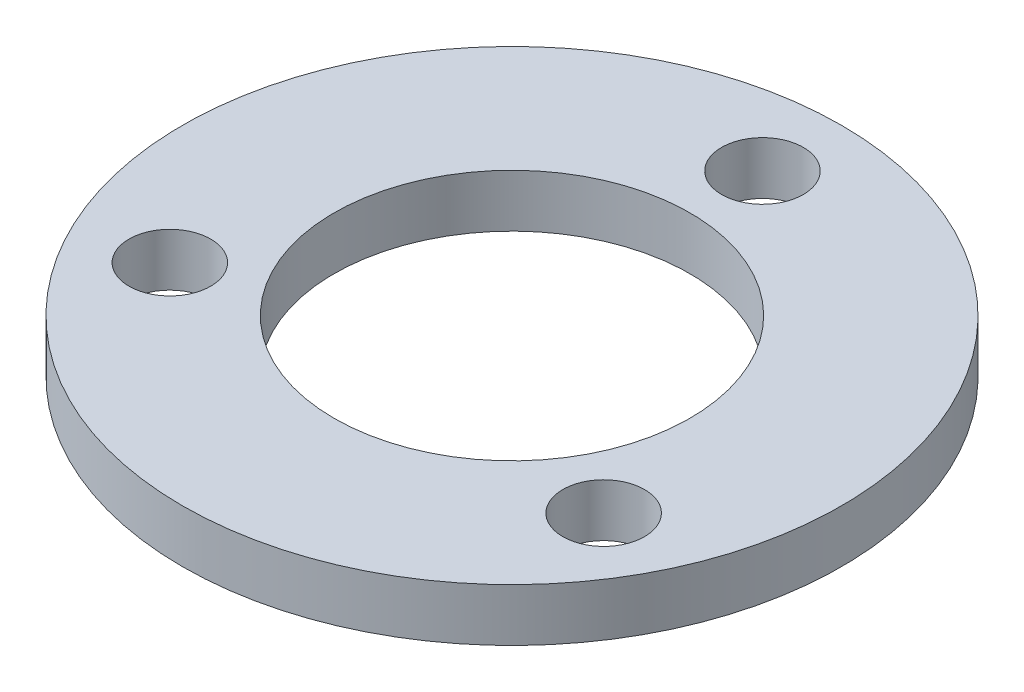
SolidWorks part; units mm, degrees
material "环氧树脂,未充填"
ref_plane "前视基准面" through (0, 0, 0) normal (0, 0, 1) x (1, 0, 0)
ref_plane "上视基准面" through (0, 0, 0) normal (0, 1, 0) x (1, 0, 0)
ref_plane "右视基准面" through (0, 0, 0) normal (1, 0, 0) x (0, 0, -1)
sketch "草图2" plane through (0, 0, 0) normal (0, 1, 0) x (1, 0, 0)
  circle A0 centre (0, 0) radius 6.75
  circle A1 centre (0, 0) radius 12.5
  dimension "D1" = 13.5
  dimension "D2" = 25
extrude "凸台-拉伸1" add sketch "草图2" along normal blind 2
sketch "草图3" plane through (0, 2, 0) normal (0, 1, 0) x (1, 0, 0)
  line L0 (0, 12.5) -> (0, 0) construction
  circle A0 centre (0, 0) radius 12.5 construction
  circle A1 centre (0, 9.5) radius 1.55
  circle A2 centre (8.2272, -4.75) radius 1.55
  circle A3 centre (-8.2272, -4.75) radius 1.55
  point P13 (0, 0)
  dimension "D1" = 9.5
  dimension "D2" = 3.1
  dimension "D3" = 3
extrude "切除-拉伸1" cut sketch "草图3" against normal through all
